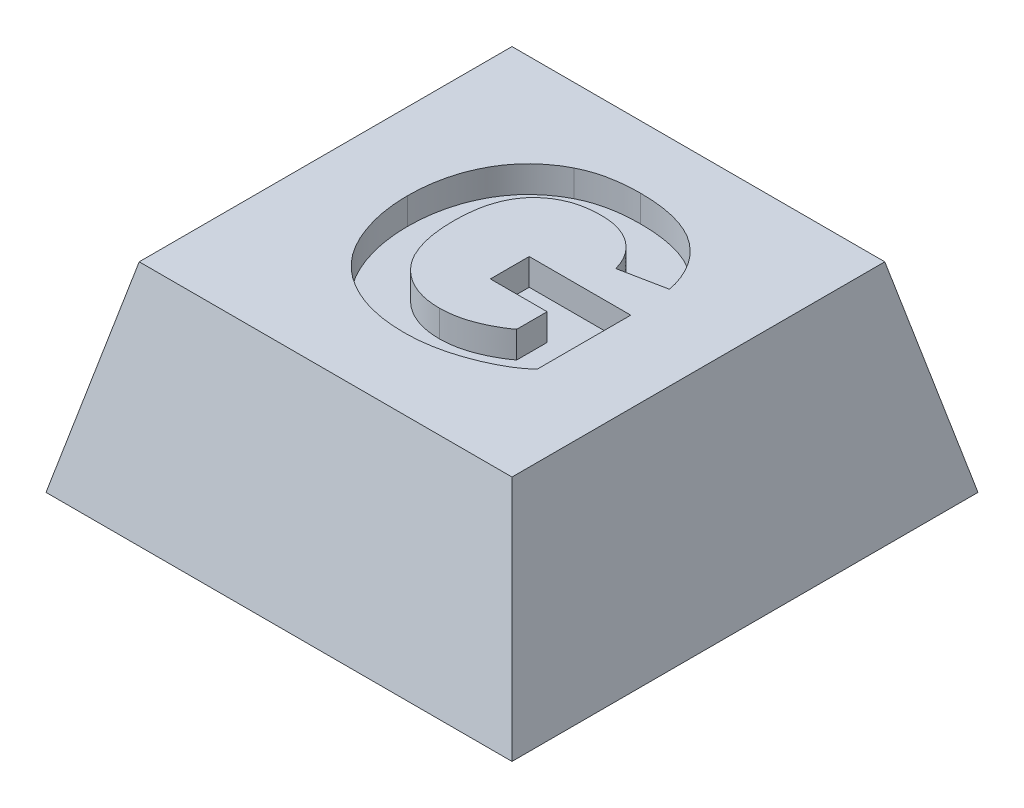
SolidWorks part; units mm, degrees
ref_plane "Front Plane" through (0, 0, 0) normal (0, 0, 1) x (1, 0, 0)
ref_plane "Top Plane" through (0, 0, 0) normal (0, 1, 0) x (1, 0, 0)
ref_plane "Right Plane" through (0, 0, 0) normal (1, 0, 0) x (0, 0, -1)
sketch "Sketch1" plane through (0, 0, 0) normal (0, 1, 0) x (1, 0, 0)
  line L1 (0, 0) -> (7, 0)
  line L2 (0, 0) -> (0, 7)
  line L3 (0, 7) -> (7, 7)
  line L4 (7, 0) -> (7, 7)
  dimension "D1" = 7
  dimension "D2" = 7
extrude "Boss-Extrude1" add sketch "Sketch1" along normal blind 3
sketch "Sketch2" plane through (0, 0, 0) normal (0, 0, 1) x (1, 0, 0)
  line L0 (0, 0) -> (0.7, 3)
  line L1 (0, 3) -> (7, 3) construction
  line L2 (0.7, 3) -> (0, 3)
  line L3 (0, 3) -> (0, 0)
  line L4 (7, 0) -> (6.3, 3)
  line L5 (6.3, 3) -> (7, 3)
  line L6 (7, 3) -> (7, 0)
  dimension "D1" = 0.7
  dimension "D2" = 0.7
extrude "Cut-Extrude1" cut sketch "Sketch2" against normal blind 7
sketch "Sketch3" plane through (0, 0, 0) normal (1, 0, 0) x (0, 0, -1)
  line L0 (0, 0) -> (0.7, 3)
  line L1 (7, 3) -> (0, 3) construction
  line L2 (0.7, 3) -> (0, 3)
  line L3 (0, 3) -> (0, 0)
  line L4 (7, 3) -> (6.3, 3)
  line L5 (6.3, 3) -> (7, 0)
  line L6 (7, 3) -> (7, 0)
  dimension "D1" = 0.7
  dimension "D2" = 0.7
extrude "Cut-Extrude2" cut sketch "Sketch3" along normal blind 11
sketch "Sketch4" plane through (0, 0, 0) normal (0, -1, 0) x (1, 0, 0)
  line L0 (3.5, 0) -> (3.5, -7) construction
  line L1 (0, 0) -> (7, 0) construction
  line L2 (7, -7) -> (0, -7) construction
  line L3 (0, -3.5) -> (7, -3.5) construction
  line L4 (0, -7) -> (0, 0) construction
  line L5 (7, 0) -> (7, -7) construction
  circle A0 centre (3.5, -3.5) radius 1.8
  dimension "D1" = 3.6
extrude "Cut-Extrude3" cut sketch "Sketch4" against normal blind 0.8
sketch "Sketch5" plane through (0, 3, 0) normal (0, 1, 0) x (1, 0, 0)
  text T0 "G" font "Arial" height 3.5
extrude "Cut-Extrude4" cut sketch "Sketch5" against normal blind 0.4
